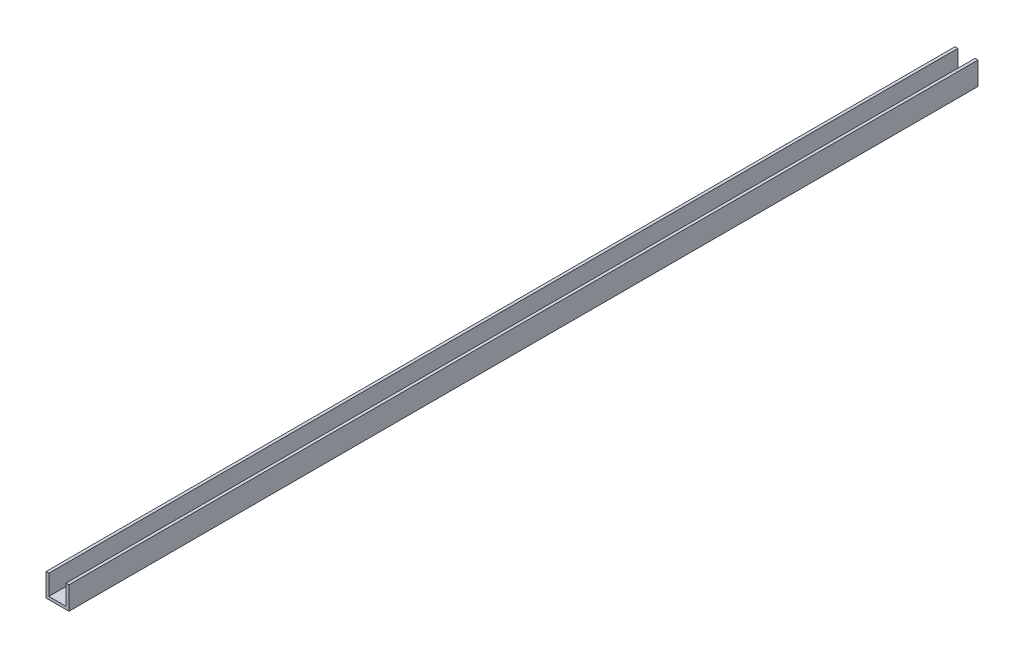
SolidWorks part; units mm, degrees
ref_plane "Front Plane" through (0, 0, 0) normal (0, 0, 1) x (1, 0, 0)
ref_plane "Top Plane" through (0, 0, 0) normal (0, 1, 0) x (1, 0, 0)
ref_plane "Right Plane" through (0, 0, 0) normal (1, 0, 0) x (0, 0, -1)
sketch "Sketch1" plane through (0, 0, 0) normal (0, 0, 1) x (1, 0, 0)
  line L0 (-10.5, 12) -> (-12, 12)
  line L1 (0, 0) -> (-12, 0)
  line L2 (0, 0) -> (0, 12)
  line L3 (0, 12) -> (-1.5, 12)
  line L4 (-12, 0) -> (-12, 12)
  line L6 (-10.5, 12) -> (-10.5, 1.5)
  line L7 (-10.5, 1.5) -> (-1.5, 1.5)
  line L8 (-1.5, 12) -> (-1.5, 1.5)
  dimension "D1" = 12
  dimension "D2" = 12
  dimension "D3" = 1.5
  dimension "D4" = 1.5
  dimension "D5" = 1.5
extrude "Boss-Extrude1" add sketch "Sketch1" along normal blind 475
sketch "Sketch2" plane through (0, 1.5, 0) normal (0, 1, 0) x (1, 0, 0)
  line L0 (-6, 0) -> (-6, -475) construction
  line L1 (-1.5, 0) -> (-10.5, 0) construction
  line L2 (-1.5, -475) -> (-10.5, -475) construction
  circle A0 centre (-6, -6) radius 2.5
  dimension "D1" = 5
  dimension "D2" = 6
extrude "Cut-Extrude1" cut sketch "Sketch2" against normal blind 10
sketch "Sketch3" plane through (0, 1.5, 0) normal (0, 1, 0) x (1, 0, 0)
  line L0 (-6, -475) -> (-6, 0) construction
  line L1 (-1.5, -475) -> (-10.5, -475) construction
  line L2 (-1.5, 0) -> (-10.5, 0) construction
  circle A0 centre (-6, -255) radius 4
  dimension "D1" = 8
  dimension "D2" = 220
